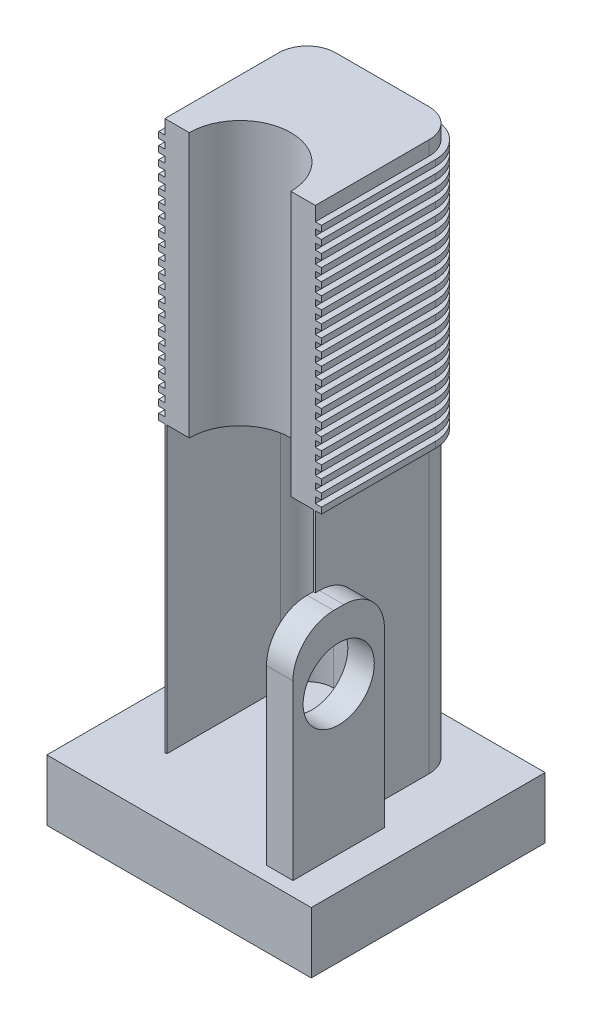
SolidWorks part; units mm, degrees
material "Plain Carbon Steel"
ref_plane "Front Plane" through (0, 0, 0) normal (0, 0, 1) x (1, 0, 0)
ref_plane "Top Plane" through (0, 0, 0) normal (0, 1, 0) x (1, 0, 0)
ref_plane "Right Plane" through (0, 0, 0) normal (1, 0, 0) x (0, 0, -1)
sketch "Sketch1" plane through (0, 0, 0) normal (0, 1, 0) x (1, 0, 0)
  line L0 (25, 0) -> (37, 0)
  line L1 (37, 0) -> (37, 56)
  line L2 (23, 70) -> (-23, 70)
  line L3 (0, 0) -> (0, 45.2197) construction
  line L4 (-25, 0) -> (-37, 0)
  line L5 (-37, 0) -> (-37, 56)
  arc A0 (25, 0) -> (-25, 0) centre (0, 0) ccw
  arc A1 (37, 56) -> (23, 70) centre (23, 56) ccw
  arc A2 (-37, 56) -> (-23, 70) centre (-23, 56) cw
  point P11 (0, 70)
  point P13 (37, 70)
  point P16 (-37, 70)
  dimension "D1" = 50
  dimension "D4" = 14
  dimension "D2" = 12
  dimension "D3" = 70
extrude "Boss-Extrude1" add sketch "Sketch1" along normal blind 90 and the other way blind 40
sketch "Sketch3" plane through (0, -40, 0) normal (0, -1, 0) x (1, 0, 0)
  line L0 (40, -56) -> (40, 0)
  line L2 (40, -56) -> (40, 3) construction
  line L3 (-40, 0) -> (-40, -56)
  line L4 (-23, -73) -> (23, -73)
  line L5 (-25, 0) -> (-37, 0)
  line L6 (-37, 0) -> (-37, -56)
  line L7 (-23, -70) -> (23, -70)
  line L8 (37, -56) -> (37, 0)
  line L9 (37, 0) -> (25, 0)
  line L10 (-25, 0) -> (-40, 0)
  line L11 (-37, 0) -> (-37, -56)
  line L12 (-23, -70) -> (23, -70)
  line L13 (37, -56) -> (37, 0)
  line L14 (40, 0) -> (25, 0)
  line L15 (-25, 0) -> (-37, 0) construction
  line L16 (37, 0) -> (25, 0) construction
  line L17 (-21.7945, 3) -> (-40, 3) construction
  line L18 (-40, 3) -> (-40, -56) construction
  line L19 (40, 3) -> (21.7945, 3) construction
  arc A1 (-40, -56) -> (-23, -73) centre (-23, -56) ccw
  arc A2 (23, -73) -> (40, -56) centre (23, -56) ccw
  arc A3 (-25, 0) -> (25, 0) centre (0, 0) ccw
  arc A4 (-37, -56) -> (-23, -70) centre (-23, -56) ccw
  arc A5 (23, -70) -> (37, -56) centre (23, -56) ccw
  arc A6 (-25, 0) -> (25, 0) centre (0, 0) ccw
  arc A7 (-37, -56) -> (-23, -70) centre (-23, -56) ccw
  arc A8 (23, -70) -> (37, -56) centre (23, -56) ccw
  arc A9 (-21.7945, 3) -> (21.7945, 3) centre (0, 0) ccw construction
  line M11 (-37, 0) -> (-37, -56)
  arc M12 (-37, -56) -> (-23, -70) centre (-23, -56) ccw
  line M13 (-23, -70) -> (23, -70)
  arc M14 (23, -70) -> (37, -56) centre (23, -56) ccw
  line M15 (37, -56) -> (37, 0)
  dimension "D1" = 0
  dimension "D2" = 3
extrude "Boss-Extrude2" add sketch "Sketch3" against normal blind 3 contours L4 A2 L0 L14 L10 L3 A1 M15 M14 M13 M12 M11
pattern_linear "LPattern1" count 21 spacing 6 along (0, 1, 0) of "Boss-Extrude2"
sketch "Sketch6" plane through (0, 0, 0) normal (0, 1, 0) x (1, 0, 0)
  line L0 (-37, 0) -> (-37, 56)
  line L1 (37, 0) -> (37, 56)
  line L2 (-23, 70) -> (23, 70)
  line L3 (-36, 0) -> (-36, 56)
  line L4 (-23, 69) -> (23, 69)
  line L5 (36, 0) -> (36, 56)
  line L6 (-37, 0) -> (-36, 0)
  line L7 (37, 0) -> (36, 0)
  arc A0 (-37, 56) -> (-23, 70) centre (-23, 56) cw
  arc A1 (23, 70) -> (37, 56) centre (23, 56) cw
  arc A2 (-36, 56) -> (-23, 69) centre (-23, 56) cw
  arc A3 (23, 69) -> (36, 56) centre (23, 56) cw
  dimension "D1" = 1
extrude "Boss-Extrude3" add sketch "Sketch6" against normal blind 180
sketch "Sketch7" plane through (37, 0, 0) normal (1, 0, 0) x (0, 0, -1)
  line L0 (0, -180) -> (0, -40) construction
  circle A0 centre (0, -115.5371) radius 24.1404
sketch "Sketch8" plane through (0, -180, 0) normal (0, -1, 0) x (1, 0, 0)
  line L0 (40, -56) -> (40, 0) construction
  line L1 (-65, 0) -> (65, 0) construction
  line L2 (-65, 0) -> (-65, -85)
  line L3 (-65, -85) -> (65, -85)
  line L4 (65, 0) -> (65, -85)
  line L5 (65, -42.5) -> (40, -42.5) construction
  line L6 (-40, -42.5) -> (-65, -42.5) construction
  line L7 (-40, 0) -> (-40, -56) construction
  line L8 (23, -70) -> (-23, -70) construction
  line L9 (37, 0) -> (40, 0) construction
  line L10 (-65, 0) -> (-65, 30)
  line L11 (-65, 30) -> (65, 30)
  line L12 (65, 30) -> (65, 0)
  dimension "D1" = 25
  dimension "D2" = 15
  dimension "D3" = 30
extrude "Boss-Extrude4" add sketch "Sketch8" along normal blind 30
sketch "Sketch10" plane through (0, -180, 0) normal (0, 1, 0) x (1, 0, 0)
  line L1 (36, 22) -> (49, 22)
  line L2 (36, 22) -> (36, -23)
  line L3 (36, -23) -> (49, -23)
  line L4 (49, 22) -> (49, -23)
  line L5 (65, -30) -> (-65, -30) construction
  line L6 (36, 56) -> (36, 0) construction
  dimension "D1" = 45
  dimension "D2" = 7
  dimension "D3" = 13
extrude "Boss-Extrude6" add sketch "Sketch10" along normal blind 105
fillet "Fillet1" radius 20 2 edges at (43, -75, -22) (42.5, -75, 23)
mirror "Mirror1" [suppressed] about plane through (0, 0, 0) normal (1, 0, 0)
sketch "Sketch11" plane through (49, 0, 0) normal (1, 0, 0) x (0, 0, -1)
  line L0 (-23, -107.5) -> (22, -107.5) construction
  line L1 (-23, -95) -> (-23, -180) construction
  line L2 (22, -95) -> (22, -180) construction
  line L3 (-3, -75) -> (2, -75) construction
  circle A0 centre (-0.5, -107.5) radius 17.5
  dimension "D1" = 35
  dimension "D2" = 32.5
extrude "Cut-Extrude1" cut sketch "Sketch11" against normal up to next
